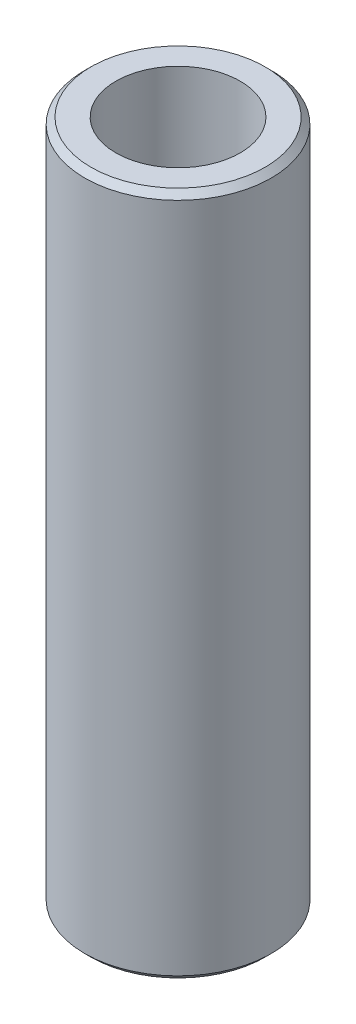
SolidWorks part; units mm, degrees
ref_plane "Front Plane" through (0, 0, 0) normal (0, 0, 1) x (1, 0, 0)
ref_plane "Top Plane" through (0, 0, 0) normal (0, 1, 0) x (1, 0, 0)
ref_plane "Right Plane" through (0, 0, 0) normal (1, 0, 0) x (0, 0, -1)
sketch "Sketch1" plane through (0, 0, 0) normal (0, 1, 0) x (1, 0, 0)
  circle A0 centre (0, 0) radius 5
  circle A1 centre (0, 0) radius 7.5
  dimension "D1" = 10
  dimension "D2" = 15
extrude "Corpo Ø15×55" add sketch "Sketch1" along normal blind 55
chamfer "Chanfros 0.5×45°" distance 0.5 angle 45 2 edges at (0, 0, 7.5) (0, 55, 7.5)
